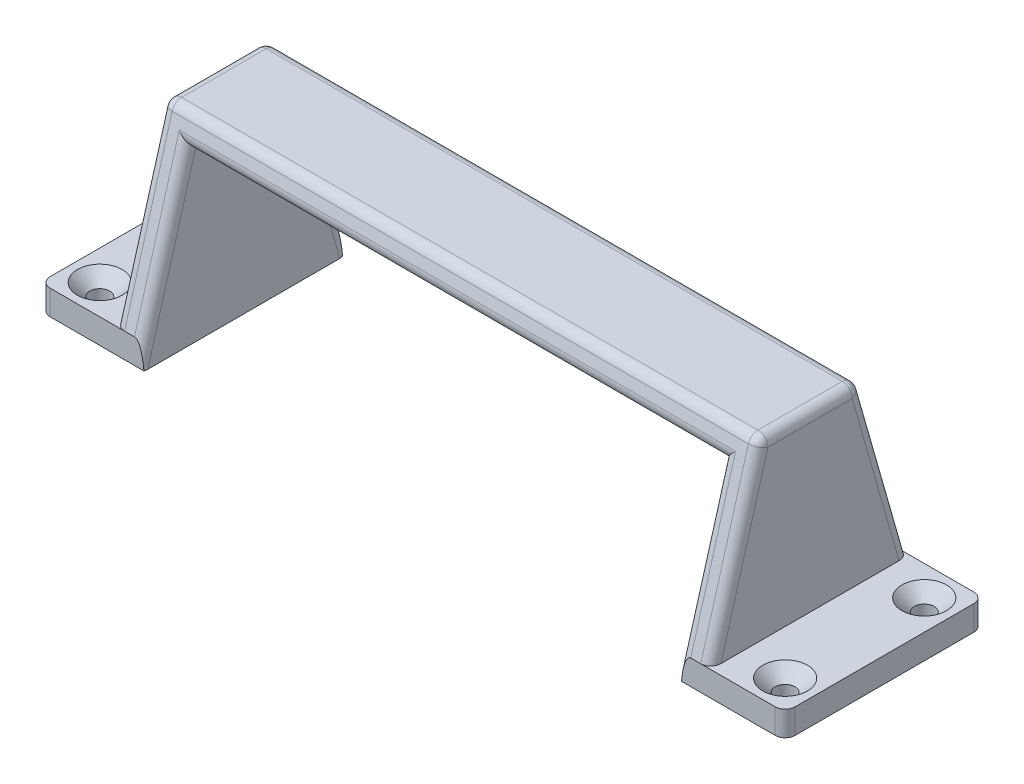
SolidWorks part; units mm, degrees
ref_plane "前视基准面" through (0, 0, 0) normal (0, 0, 1) x (1, 0, 0)
ref_plane "上视基准面" through (0, 0, 0) normal (0, 1, 0) x (1, 0, 0)
ref_plane "右视基准面" through (0, 0, 0) normal (1, 0, 0) x (0, 0, -1)
sketch "草图1" plane through (0, 0, 0) normal (0, 0, 1) x (1, 0, 0)
  line L1 (0, 0) -> (150, 0)
  line L2 (0, 0) -> (0, 40)
  line L3 (0, 40) -> (150, 40)
  line L4 (150, 0) -> (150, 40)
  dimension "D1" = 150
  dimension "D2" = 40
extrude "凸台-拉伸1" add sketch "草图1" along normal blind 40
sketch "草图2" plane through (0, 0, 0) normal (0, 0, -1) x (-1, 0, 0)
  line L0 (0, 0) -> (-150, 0) construction
  line L1 (-150, 40) -> (-135, 40)
  line L2 (-150, 40) -> (-150, 5)
  line L3 (-150, 5) -> (-135, 5)
  line L4 (-135, 40) -> (-135, 5)
  line L5 (0, 40) -> (-15, 40)
  line L6 (0, 40) -> (0, 5)
  line L7 (0, 5) -> (-15, 5)
  line L8 (-15, 40) -> (-15, 5)
  dimension "D1" = 5
  dimension "D2" = 15
extrude "切除-拉伸1" cut sketch "草图2" against normal up to next
sketch "草图3" plane through (0, 0, 0) normal (0, 0, -1) x (-1, 0, 0)
  line L0 (0, 0) -> (-150, 0) construction
  line L1 (-129, 0) -> (-21, 0)
  line L2 (-129, 0) -> (-129, 34)
  line L3 (-129, 34) -> (-21, 34)
  line L4 (-21, 0) -> (-21, 34)
  line L5 (-135, 40) -> (-15, 40) construction
  line L6 (-15, 40) -> (-15, 5) construction
  point P4 (-75, 0)
  point P7 (-75, 0)
  dimension "D1" = 6
  dimension "D2" = 6
extrude "切除-拉伸2" cut sketch "草图3" against normal up to next
sketch "草图4" plane through (135, 0, 0) normal (1, 0, 0) x (0, 0, -1)
  line L0 (-40, 40) -> (-40, 5)
  line L1 (-40, 5) -> (-30, 40)
  line L2 (-30, 40) -> (-40, 40)
  line L4 (-10, 40) -> (0, 40)
  line L5 (0, 40) -> (0, 5)
  line L6 (0, 5) -> (-10, 40)
  line L9 (-40, 40) -> (0, 40) construction
  point P5 (0, 0)
  point P7 (0, 0)
  dimension "D1" = 10
extrude "切除-拉伸3" cut sketch "草图4" against normal up to surface (120 mm away) up to face at (15, 22.5, 20)
sketch "草图5" plane through (0, 0, 0) normal (0, -1, 0) x (1, 0, 0)
  line L0 (0, 0) -> (21, 0) construction
  line L1 (0, 40) -> (0, 0) construction
  line L2 (0, 40) -> (21, 40) construction
  circle A0 centre (6, 6) radius 2
  circle A1 centre (6, 34) radius 2
  point P10 (0, 0)
  dimension "D1" = 6
  dimension "D2" = 6
  dimension "D3" = 6
extrude "切除-拉伸4" cut sketch "草图5" against normal up to surface (5 mm away) up to face at (7.5, 5, 20)
ref_plane "基准面1" through (75, 0, 0) normal (-1, 0, 0) x (0, 0, 1)
mirror "镜向5" about plane through (75, 0, 0) normal (-1, 0, 0) of "切除-拉伸4"
chamfer "倒角1" distance 2.5 angle 45 4 edges at (8, 5, 34) (8, 5, 6) (146, 5, 34) (146, 5, 6)
fillet "圆角2" radius 2 14 edges at (135, 22.5, 5) (135, 40, 20) (135, 22.5, 35) (15, 22.5, 35) (15, 40, 20) (15, 22.5, 5) (75, 40, 10) (75, 40, 30) (21, 19.5, 4.1429) (75, 34, 8.2857) (129, 19.5, 4.1429) (129, 19.5, 35.8571) (21, 19.5, 35.8571) (75, 34, 31.7143)
fillet "圆角3" radius 2 4 edges at (150, 2.5, 0) (150, 2.5, 40) (0, 2.5, 40) (0, 2.5, 0)
